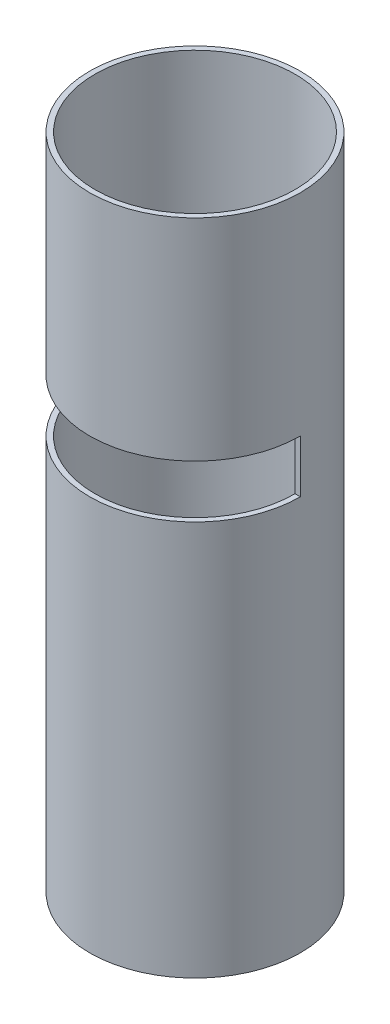
SolidWorks part; units mm, degrees
ref_plane "Front Plane" through (0, 0, 0) normal (0, 0, 1) x (1, 0, 0)
ref_plane "Top Plane" through (0, 0, 0) normal (0, 1, 0) x (1, 0, 0)
ref_plane "Right Plane" through (0, 0, 0) normal (1, 0, 0) x (0, 0, -1)
sketch "Sketch1" plane through (0, 0, 0) normal (0, 1, 0) x (1, 0, 0)
  circle A0 centre (0, 0) radius 38
  circle A1 centre (0, 0) radius 40
  dimension "D1" = 2
  dimension "D2" = 80
extrude "Boss-Extrude1" add sketch "Sketch1" along normal blind 250
sketch "Sketch2" plane through (0, 0, 0) normal (0, 0, 1) x (1, 0, 0)
  line L0 (-40, 250) -> (-40, 0) construction
  line L1 (-40, 170) -> (40, 170)
  line L2 (-40, 170) -> (-40, 150)
  line L3 (-40, 150) -> (40, 150)
  line L4 (40, 170) -> (40, 150)
  line L5 (40, 0) -> (40, 250) construction
  dimension "D1" = 150
  dimension "D2" = 20
extrude "Cut-Extrude2" cut sketch "Sketch2" along normal through all
